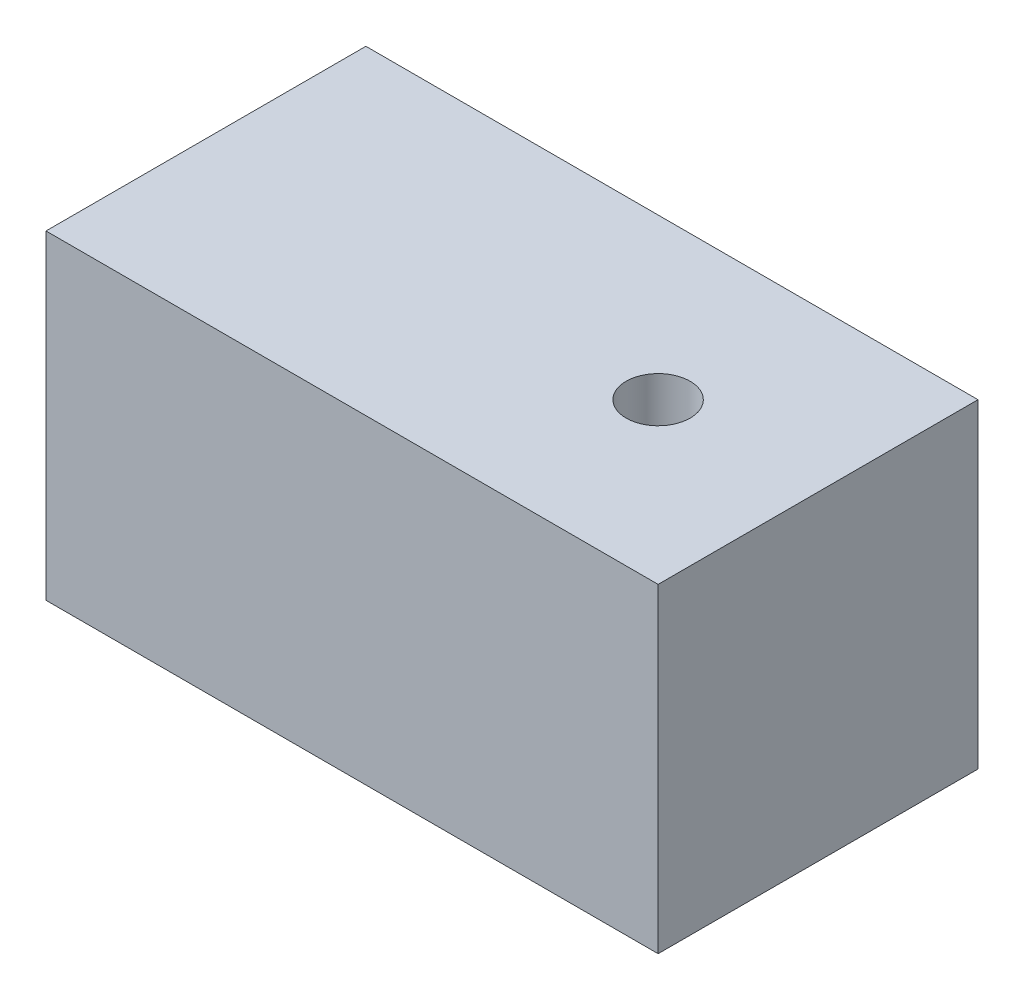
SolidWorks part; units mm, degrees
ref_plane "Front Plane" through (0, 0, 0) normal (0, 0, 1) x (1, 0, 0)
ref_plane "Top Plane" through (0, 0, 0) normal (0, 1, 0) x (1, 0, 0)
ref_plane "Right Plane" through (0, 0, 0) normal (1, 0, 0) x (0, 0, -1)
sketch "Sketch1" plane through (0, 0, 0) normal (0, 1, 0) x (1, 0, 0)
  line L1 (0, 0) -> (24.3032, 0)
  line L2 (0, 0) -> (0, 12.7)
  line L3 (0, 12.7) -> (24.3032, 12.7)
  line L4 (24.3032, 0) -> (24.3032, 12.7)
  dimension "D1" = 12.7
extrude "Boss-Extrude1" add sketch "Sketch1" along normal blind 12.7
sketch "Sketch2" plane through (0, 0, 0) normal (-1, 0, 0) x (0, 0, 1)
  line L0 (-12.7, 0) -> (0, 0) construction
  line L1 (-12.7, 12.7) -> (-12.7, 0) construction
  circle A0 centre (-6.3622, 6.35) radius 1.75
  dimension "D1" = 3.5
  dimension "D3" = 6.3378
  dimension "D2" = 6.35
extrude "Cut-Extrude1" cut sketch "Sketch2" against normal blind 14.224
sketch "Sketch3" plane through (0, 0, 0) normal (0, 1, 0) x (1, 0, 0)
  line L0 (24.3032, 12.7) -> (11.6032, 0) construction
  line L1 (0, 0) -> (24.3032, 0) construction
  circle A0 centre (17.9532, 6.35) radius 1.27
  dimension "D1" = 2.54
extrude "Cut-Extrude2" cut sketch "Sketch3" along normal through all
